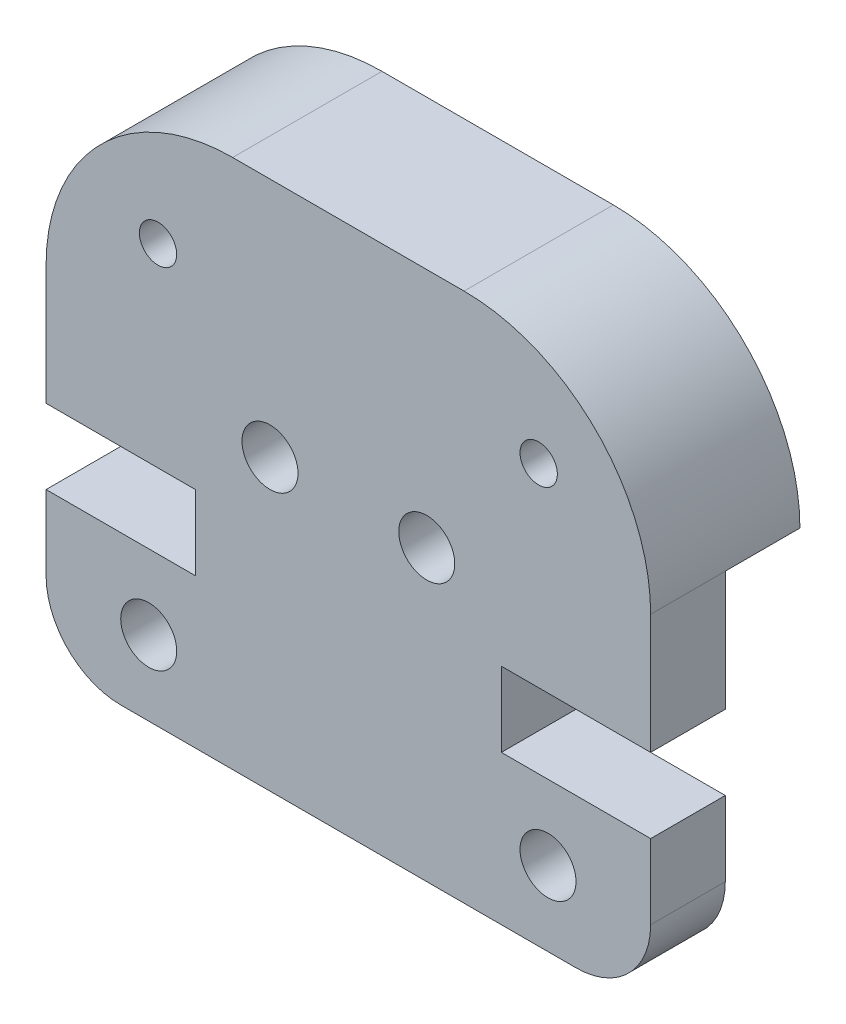
SolidWorks part; units mm, degrees
ref_plane "Front Plane" through (0, 0, 0) normal (0, 0, 1) x (1, 0, 0)
ref_plane "Top Plane" through (0, 0, 0) normal (0, 1, 0) x (1, 0, 0)
ref_plane "Right Plane" through (0, 0, 0) normal (1, 0, 0) x (0, 0, -1)
sketch "Sketch1" plane through (0, 0, 0) normal (0, 0, 1) x (1, 0, 0)
  line L0 (8.1, 14.205) -> (8.1, 0) construction
  line L1 (12.2, 4) -> (16.2, 4)
  line L2 (12.2, 6) -> (12.2, 4)
  line L3 (16.2, 6) -> (12.2, 6)
  line L4 (16.2, 2) -> (16.2, 4)
  line L5 (16.2, 9.205) -> (16.2, 6)
  line L14 (0, 9.205) -> (0, 6)
  line L15 (5, 14.205) -> (11.2, 14.205)
  line L16 (2, 0) -> (14.2, 0)
  line L18 (0, 2) -> (0, 4)
  line L19 (0, 6) -> (4, 6)
  line L21 (4, 6) -> (4, 4)
  line L22 (4, 4) -> (0, 4)
  circle A0 centre (13.45, 2) radius 0.75
  arc A1 (16.2, 2) -> (14.2, 0) centre (14.2, 2) cw
  circle A2 centre (13.2, 11.205) radius 0.5
  arc A3 (11.2, 14.205) -> (16.2, 9.205) centre (11.2, 9.205) cw
  circle A4 centre (10.2, 7.75) radius 0.75
  circle A11 centre (6, 7.75) radius 0.75
  arc A13 (5, 14.205) -> (0, 9.205) centre (5, 9.205) ccw
  circle A15 centre (3, 11.205) radius 0.5
  arc A17 (0, 2) -> (2, 0) centre (2, 2) ccw
  circle A19 centre (2.75, 2) radius 0.75
  dimension "D1" = 1
  dimension "D2" = 1.5
  dimension "D3" = 5
  dimension "D4" = 2
  dimension "D5" = 3
  dimension "D6" = 6
  dimension "D7" = 8.1
  dimension "D8" = 7.75
  dimension "D9" = 3
  dimension "D10" = 14.205
extrude "Boss-Extrude1" add sketch "Sketch1" along normal blind 4
sketch "Sketch2" plane through (0, 0, 0) normal (0, 0, -1) x (-1, 0, 0)
  line L0 (0, 0) -> (0, 9.205)
  line L1 (0, 9.205) -> (-16.2, 9.205)
  line L2 (-16.2, 9.205) -> (-16.2, 0)
  line L3 (-16.2, 0) -> (0, 0)
extrude "Cut-Extrude1" cut sketch "Sketch2" against normal blind 2
equation "\"D7@Sketch1\"= \"fingerWidth@parametersSketch@prostheticParameters.SLDPRT\" / 2 'DIP width"
equation "\"D10@Sketch1\"= \"HL@parametersSketch@prostheticParameters.SLDPRT\" * 0.093 - 3 'DIP length - Sil. Sht DIP"
